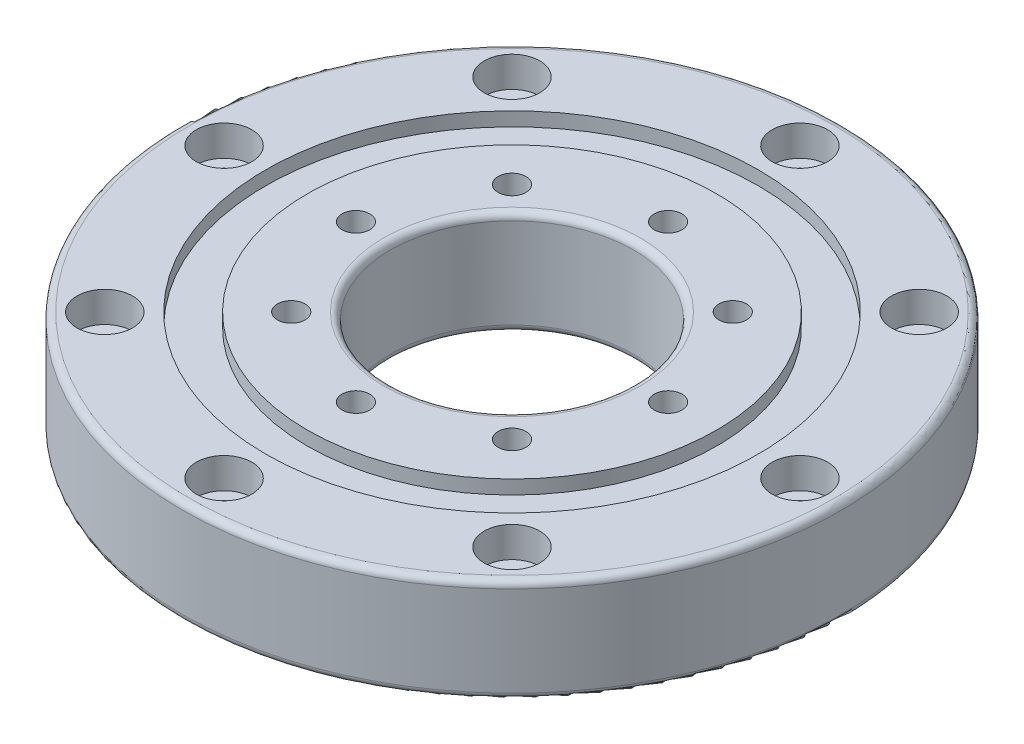
SolidWorks part; units mm, degrees
ref_plane "前视基准面" through (0, 0, 0) normal (0, 0, 1) x (1, 0, 0)
ref_plane "上视基准面" through (0, 0, 0) normal (0, 1, 0) x (1, 0, 0)
ref_plane "右视基准面" through (0, 0, 0) normal (1, 0, 0) x (0, 0, -1)
other "Configuration Table"
sketch "草图1" plane through (0, 0, 0) normal (0, 0, 1) x (1, 0, 0)
  line L0 (0, 50.7445) -> (0, -29.9743) construction
  line L1 (-55.2344, 0) -> (67.4844, 0) construction
  line L2 (17.5, 7.5) -> (17.5, -7.5)
  line L3 (17.5, 7.5) -> (29.5, 7.5)
  line L4 (29.5, 7.5) -> (29.5, 5.5)
  line L5 (29.5, 5.5) -> (35.5, 5.5)
  line L6 (35.5, 5.5) -> (35.5, 7.5)
  line L7 (35.5, 7.5) -> (47.5, 7.5)
  line L8 (47.5, 7.5) -> (47.5, -7.5)
  line L9 (35.5, -7.5) -> (47.5, -7.5)
  line L10 (35.5, -5.5) -> (35.5, -7.5)
  line L11 (29.5, -5.5) -> (35.5, -5.5)
  line L12 (29.5, -7.5) -> (29.5, -5.5)
  line L13 (17.5, -7.5) -> (29.5, -7.5)
  point P14 (47.5, 0)
  point P19 (17.5, 0)
  dimension "D1" = 17.5
  dimension "D2" = 47.5
  dimension "D3" = 12
  dimension "D4" = 12
  dimension "D5" = 2
  dimension "D6" = 7.5
revolve "旋转1" add sketch "草图1" angle 360 about L0
sketch "草图2" plane through (0, 7.5, 0) normal (0, 1, 0) x (1, 0, 0)
  line L0 (0, 0) -> (0, 50.2087) construction
  circle A0 centre (0, 0) radius 22.5 construction
  circle A1 centre (0, 0) radius 41.5 construction
  circle A2 centre (0, 22.5) radius 2
  circle A3 centre (0, 41.5) radius 2.25
  circle A4 centre (15.9099, 15.9099) radius 2
  circle A5 centre (22.5, 0) radius 2
  circle A6 centre (15.9099, -15.9099) radius 2
  circle A7 centre (0, -22.5) radius 2
  circle A8 centre (-15.9099, -15.9099) radius 2
  circle A9 centre (-22.5, 0) radius 2
  circle A10 centre (-15.9099, 15.9099) radius 2
  circle A11 centre (29.3449, 29.3449) radius 2.25
  circle A12 centre (41.5, 0) radius 2.25
  circle A13 centre (29.3449, -29.3449) radius 2.25
  circle A14 centre (0, -41.5) radius 2.25
  circle A15 centre (-29.3449, -29.3449) radius 2.25
  circle A16 centre (-41.5, 0) radius 2.25
  circle A17 centre (-29.3449, 29.3449) radius 2.25
  point P26 (0, 0)
  point P40 (0, 0)
  dimension "D1" = 45
  dimension "D2" = 83
  dimension "D3" = 4
  dimension "D4" = 4.5
  dimension "D5" = 8
  dimension "D6" = 8
extrude "切除-拉伸1" cut sketch "草图2" against normal through all both and the other way through all
sketch "草图3" plane through (0, 7.5, 0) normal (0, 1, 0) x (1, 0, 0)
  circle A0 centre (0, 0) radius 41.5 construction
  circle A1 centre (0, 41.5) radius 4
  circle A2 centre (29.3449, 29.3449) radius 4
  circle A3 centre (41.5, 0) radius 4
  circle A4 centre (29.3449, -29.3449) radius 4
  circle A5 centre (0, -41.5) radius 4
  circle A6 centre (-29.3449, -29.3449) radius 4
  circle A7 centre (-41.5, 0) radius 4
  circle A8 centre (-29.3449, 29.3449) radius 4
  point P22 (0, 0)
  dimension "D1" = 8
  dimension "D2" = 8
extrude "切除-拉伸2" cut sketch "草图3" against normal blind 4.4
fillet "圆角1" radius 1 4 edges at (0, 7.5, 17.5) (0, -7.5, 17.5) (0, -7.5, 47.5) (0, 7.5, 47.5)
